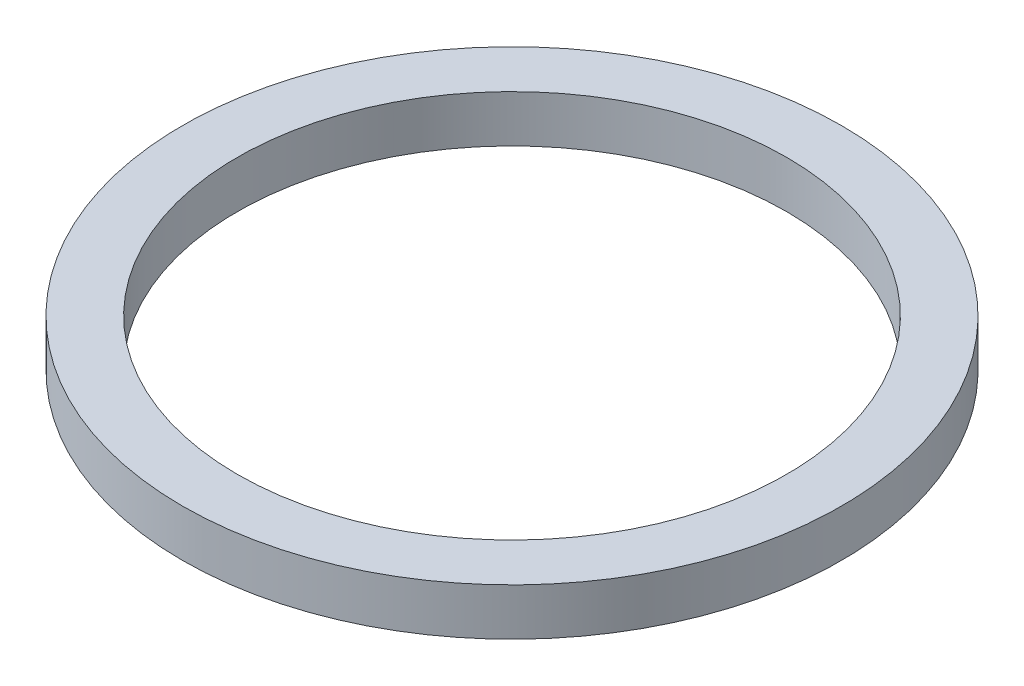
SolidWorks part; units mm, degrees
ref_plane "Front Plane" through (0, 0, 0) normal (0, 0, 1) x (1, 0, 0)
ref_plane "Top Plane" through (0, 0, 0) normal (0, 1, 0) x (1, 0, 0)
ref_plane "Right Plane" through (0, 0, 0) normal (1, 0, 0) x (0, 0, -1)
sketch "Sketch1" plane through (0, 0, 0) normal (0, 1, 0) x (1, 0, 0)
  circle A0 centre (0, 0) radius 10.5
  circle A1 centre (0, 0) radius 8.75
  dimension "D1" = 21
  dimension "D2" = 17.5
extrude "Boss-Extrude1" add sketch "Sketch1" along normal blind 1.5
